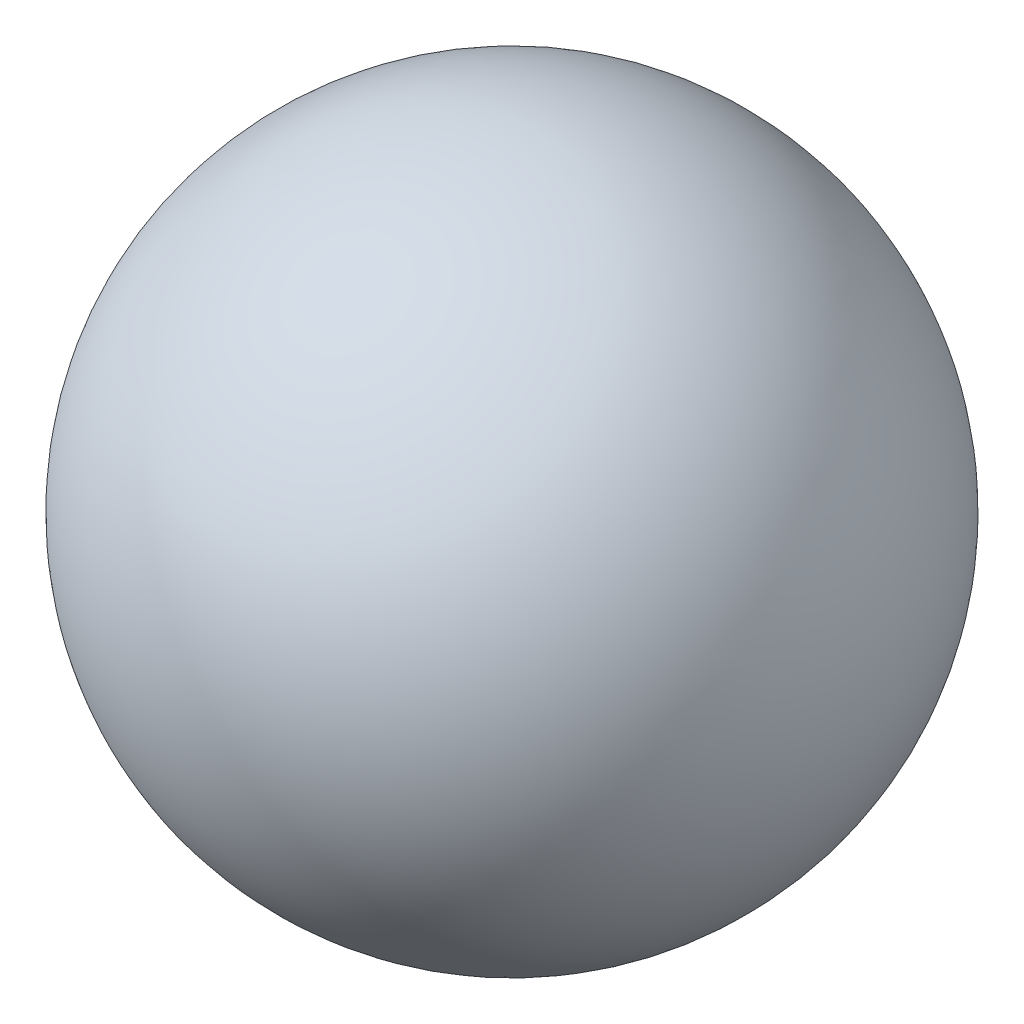
SolidWorks part; units mm, degrees
ref_plane "Front Plane" through (0, 0, 0) normal (0, 0, 1) x (1, 0, 0)
ref_plane "Top Plane" through (0, 0, 0) normal (0, 1, 0) x (1, 0, 0)
ref_plane "Right Plane" through (0, 0, 0) normal (1, 0, 0) x (0, 0, -1)
sketch "Sketch1" plane through (0, 0, 0) normal (0, 1, 0) x (1, 0, 0)
  line L0 (0, -55) -> (0, 55) construction
  line L1 (0, 33.5) -> (0, -33.5) construction
  line L2 (0, 33.5) -> (0, -33.5)
  arc A0 (0, 33.5) -> (0, -33.5) centre (0, 0) ccw
  dimension "D1" = 33.5
revolve "Revolve1" add sketch "Sketch1" angle 360 about L1
